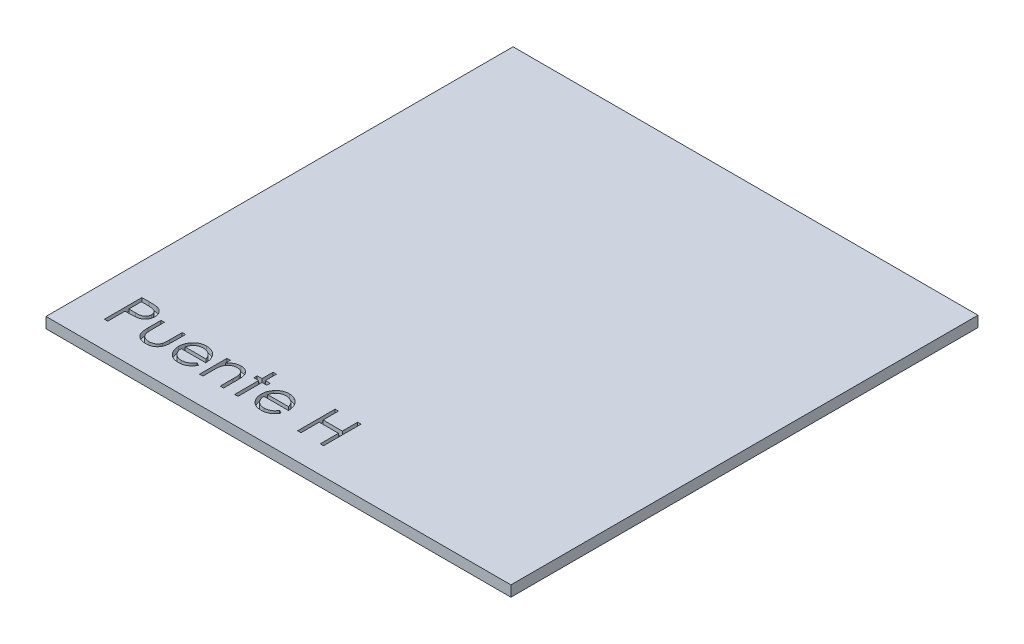
SolidWorks part; units mm, degrees
ref_plane "Alzado" through (0, 0, 0) normal (0, 0, 1) x (1, 0, 0)
ref_plane "Planta" through (0, 0, 0) normal (0, 1, 0) x (1, 0, 0)
ref_plane "Vista lateral" through (0, 0, 0) normal (1, 0, 0) x (0, 0, -1)
sketch "Sketch1" plane through (0, 0, 0) normal (0, 1, 0) x (1, 0, 0)
  line L1 (0, 0) -> (43.4, 0)
  line L2 (0, 0) -> (0, 43.6)
  line L3 (0, 43.6) -> (43.4, 43.6)
  line L4 (43.4, 0) -> (43.4, 43.6)
  dimension "D1" = 43.4
  dimension "D2" = 43.6
extrude "Boss-Extrude1" add sketch "Sketch1" along normal blind 1
sketch "Sketch2" plane through (0, 1, 0) normal (0, 1, 0) x (1, 0, 0)
  line L0 (0, 0) -> (43.4, 0) construction
  text T0 "Puente H"
  point P1 (2.5344, 2.2364)
  dimension "D1" = 2.5
  dimension "D2" = 2.5
extrude "Cut-Extrude1" cut sketch "Sketch2" against normal blind 0.5
